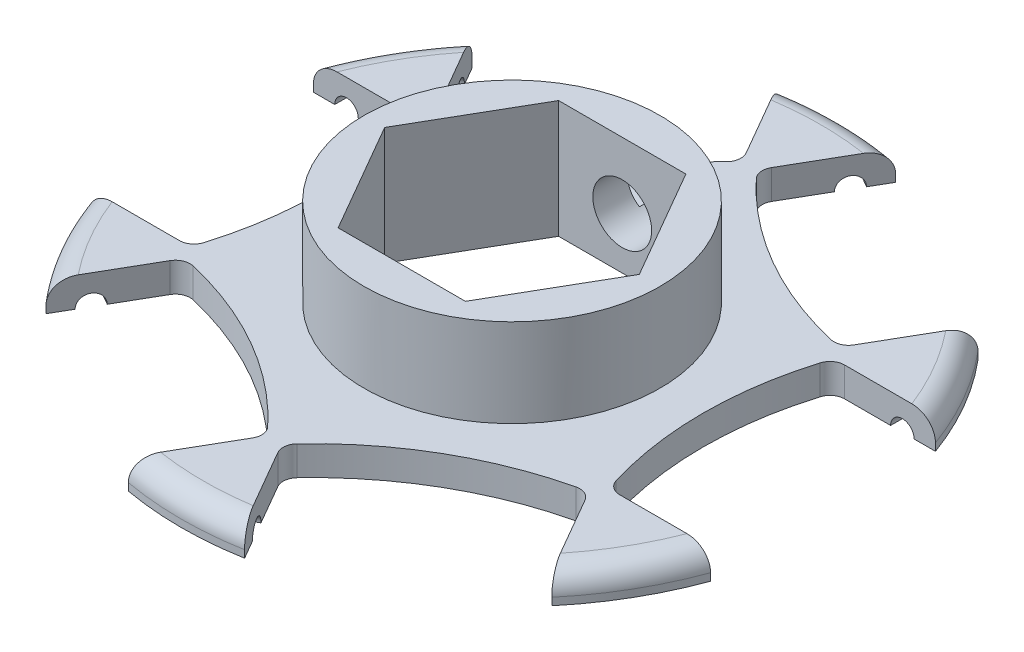
SolidWorks part; units mm, degrees
ref_plane "Ebene vorne" through (0, 0, 0) normal (0, 0, 1) x (1, 0, 0)
ref_plane "Ebene oben" through (0, 0, 0) normal (0, 1, 0) x (1, 0, 0)
ref_plane "Ebene rechts" through (0, 0, 0) normal (1, 0, 0) x (0, 0, -1)
sketch "Skizze1" plane through (0, 0, 0) normal (0, 1, 0) x (1, 0, 0)
  circle A0 centre (0, 0) radius 45
  dimension "D1" = 90
extrude "Aufsatz-Linear austragen1" add sketch "Skizze1" along normal blind 4
sketch "Skizze2" plane through (0, 4, 0) normal (0, 1, 0) x (1, 0, 0)
  line L0 (-28.5037, 15.3) -> (-71.0776, 15.3)
  line L1 (-28.5037, -15.3) -> (-71.0776, -15.3)
  line L2 (-71.0776, 15.3) -> (-71.0776, -15.3)
  circle A0 centre (-74, 0) radius 48
  circle M2 centre (0, 0) radius 45
  dimension "D1" = 74
  dimension "D2" = 96
  dimension "D3" = 30.6
  dimension "D4" = 15.3
extrude "Schnitt-Linear austragen2" cut sketch "Skizze2" against normal blind 10 contours L1 A0 L0 M2
pattern_circular "Kreismuster1" count 6 over 360 about axis through (0, 0, 0) along (0, 1, 0) of "Schnitt-Linear austragen2"
sketch "Skizze4" plane through (0, 4, 0) normal (0, 1, 0) x (1, 0, 0)
  circle A0 centre (0, 0) radius 20.15
extrude "Aufsatz-Linear austragen2" add sketch "Skizze4" along normal blind 12 contours A0
sketch "Skizze3" plane through (0, 0, 0) normal (0, -1, 0) x (1, 0, 0)
  line L1 (17.3205, 0) -> (8.6603, 15)
  line L2 (8.6603, 15) -> (-8.6603, 15)
  line L3 (-8.6603, 15) -> (-17.3205, 0)
  line L4 (-17.3205, 0) -> (-8.6603, -15)
  line L5 (-8.6603, -15) -> (8.6603, -15)
  line L6 (8.6603, -15) -> (17.3205, 0)
  circle A0 centre (0, 0) radius 15 construction
  dimension "D1" = 30
extrude "Schnitt-Linear austragen3" cut sketch "Skizze3" against normal blind 16
fillet "Verrundung1" radius 2 12 edges at (-28.5037, 2, 15.3) (-1.0017, 2, 32.335) (1.0017, 2, 32.335) (27.5021, 2, 17.035) (28.5037, 2, 15.3) (28.5037, 2, -15.3) (27.5021, 2, -17.035) (1.0017, 2, -32.335) (-1.0017, 2, -32.335) (-27.5021, 2, -17.035) (-28.5037, 2, -15.3) (-27.5021, 2, 17.035)
sketch "Skizze5" plane through (13.2502, 0, 7.65) normal (-0.866, 0, -0.5) x (-0.5, 0, 0.866)
  line L0 (-29.9647, 0) -> (-42.3191, 0) construction
  line L1 (-42.3191, 0) -> (-42.3191, 4) construction
  circle A0 centre (-37.8191, 0) radius 1.6
  dimension "D1" = 4.5
extrude "Schnitt-Linear austragen5" cut sketch "Skizze5" against normal blind 3.8 contours A0
fillet "Verrundung3" radius 0.5 1 edges at (35.4507, 1.6, -23.2023)
pattern_circular "Kreismuster2" count 6 over 360 about axis through (0, 0, 0) along (0, 1, 0) of "Schnitt-Linear austragen5", "Verrundung3"
sketch "Skizze6" plane through (0, 0, -15.3) normal (0, 0, 1) x (1, 0, 0)
  line L0 (29.9647, 0) -> (42.3191, 0) construction
  line L1 (42.3191, 0) -> (42.3191, 4) construction
  circle A0 centre (37.8191, 0) radius 1.6
  dimension "D1" = 4.5
extrude "Schnitt-Linear austragen6" cut sketch "Skizze6" against normal blind 3.8
fillet "Verrundung4" radius 0.5 1 edges at (37.8191, 1.6, -19.1)
pattern_circular "Kreismuster3" count 6 over 360 about axis through (0, 0, 0) along (0, 1, 0) of "Schnitt-Linear austragen6", "Verrundung4"
sketch "Zentrierung" plane through (0, 0, 0) normal (0, -1, 0) x (1, 0, 0)
  circle A0 centre (0, 0) radius 20
fillet "Verrundung2" radius 3 6 edges at (0, 4, -45) (-38.9711, 4, -22.5) (-38.9711, 4, 22.5) (0, 4, 45) (38.9711, 4, 22.5) (38.9711, 4, -22.5)
sketch "Skizze7" plane through (0, 0, -15) normal (0, 0, 1) x (1, 0, 0)
  line L0 (-8.6603, 0) -> (8.6603, 0) construction
  circle A0 centre (0, 7) radius 4
  dimension "D1" = 7
extrude "Schnitt-Linear austragen7" cut sketch "Skizze7" against normal blind 10
